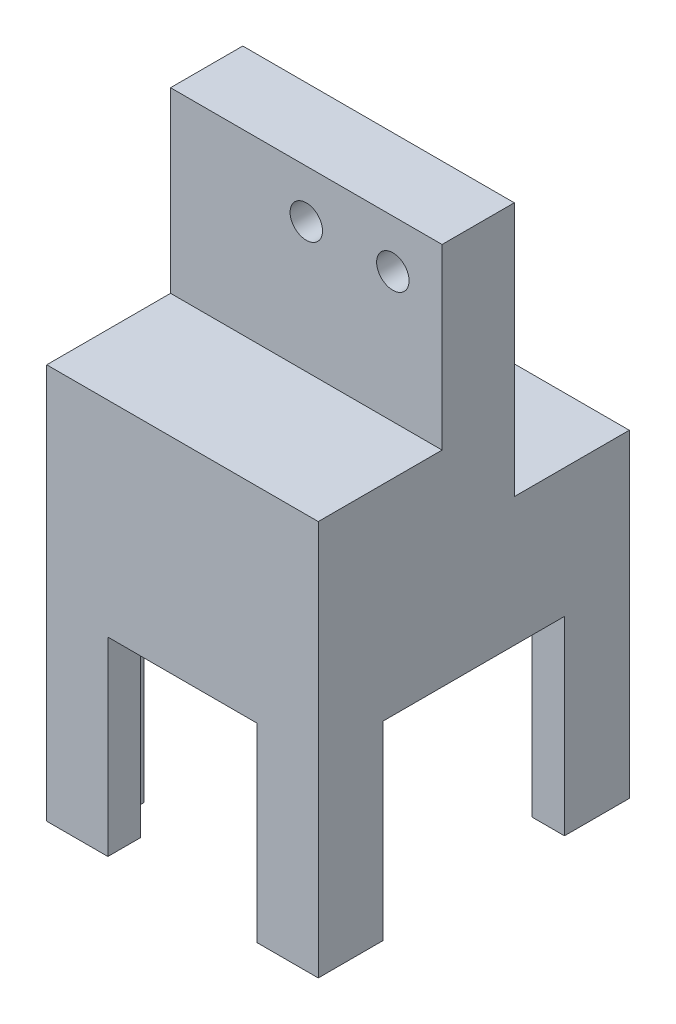
SolidWorks part; units mm, degrees
ref_plane "Front Plane" through (0, 0, 0) normal (0, 0, 1) x (1, 0, 0)
ref_plane "Top Plane" through (0, 0, 0) normal (0, 1, 0) x (1, 0, 0)
ref_plane "Right Plane" through (0, 0, 0) normal (1, 0, 0) x (0, 0, -1)
sketch "Sketch4" plane through (0, 0, 0) normal (0, 1, 0) x (1, 0, 0)
  line L1 (-12.55, 14.375) -> (12.55, 14.375)
  line L2 (-12.55, 14.375) -> (-12.55, -14.375)
  line L3 (-12.55, -14.375) -> (12.55, -14.375)
  line L4 (12.55, 14.375) -> (12.55, -14.375)
  line L5 (-12.55, 14.375) -> (12.55, -14.375) construction
  line L6 (-12.55, -14.375) -> (12.55, 14.375) construction
  point P0 (0, 0)
  dimension "D1" = 28.75
  dimension "D2" = 25.1
extrude "Boss-Extrude2" add sketch "Sketch4" along normal blind 53
sketch "Sketch5" plane through (0, 0, 0) normal (0, -1, 0) x (-1, 0, 0)
  line L0 (-12.55, -14.375) -> (-12.55, 14.375) construction
  line L1 (9.55, -11.375) -> (-9.55, -11.375)
  line L2 (9.55, -11.375) -> (9.55, 11.375)
  line L3 (9.55, 11.375) -> (-9.55, 11.375)
  line L4 (-9.55, -11.375) -> (-9.55, 11.375)
  line L5 (9.55, -11.375) -> (-9.55, 11.375) construction
  line L6 (9.55, 11.375) -> (-9.55, -11.375) construction
  line L7 (-12.55, 14.375) -> (12.55, 14.375) construction
  point P0 (0, 0)
  dimension "D1" = 22.75
  dimension "D2" = 19.1
  dimension "D3" = 3
  dimension "D4" = 3
extrude "Cut-Extrude1" cut sketch "Sketch5" against normal blind 21.67
fillet "Fillet1" radius 4.1 2 edges at (0, 21.67, -11.375) (0, 21.67, 11.375)
sketch "Sketch6" plane through (0, 21.67, 0) normal (0, -1, 0) x (-1, 0, 0)
  line L1 (1.44, 2.55) -> (-1.44, 2.55)
  line L2 (1.44, 2.55) -> (1.44, -2.55)
  line L3 (1.44, -2.55) -> (-1.44, -2.55)
  line L4 (-1.44, 2.55) -> (-1.44, -2.55)
  line L5 (1.44, 2.55) -> (-1.44, -2.55) construction
  line L6 (1.44, -2.55) -> (-1.44, 2.55) construction
  point P0 (0, 0)
  dimension "D1" = 2.88
  dimension "D2" = 5.1
extrude "Cut-Extrude2" cut sketch "Sketch6" against normal blind 4.67
sketch "Sketch7" plane through (12.55, 0, 0) normal (1, 0, 0) x (0, 0, -1)
  line L0 (-14.375, 53) -> (-14.375, 0) construction
  line L1 (-8.3848, -17.57) -> (8.3848, -17.57)
  line L2 (-8.3848, -17.57) -> (-8.3848, 17.57)
  line L3 (-8.3848, 17.57) -> (8.3848, 17.57)
  line L4 (8.3848, -17.57) -> (8.3848, 17.57)
  line L5 (-8.3848, -17.57) -> (8.3848, 17.57) construction
  line L6 (-8.3848, 17.57) -> (8.3848, -17.57) construction
  point P0 (0, 0)
  dimension "D1" = 35.14
  dimension "D2" = 5.9902
extrude "Cut-Extrude3" cut sketch "Sketch7" against normal blind 40
sketch "Sketch8" plane through (0, 0, -14.375) normal (0, 0, -1) x (-1, 0, 0)
  line L0 (12.55, 53) -> (12.55, 0) construction
  line L1 (-6.8992, -17.57) -> (6.8992, -17.57)
  line L2 (-6.8992, -17.57) -> (-6.8992, 17.57)
  line L3 (-6.8992, 17.57) -> (6.8992, 17.57)
  line L4 (6.8992, -17.57) -> (6.8992, 17.57)
  line L5 (-6.8992, -17.57) -> (6.8992, 17.57) construction
  line L6 (-6.8992, 17.57) -> (6.8992, -17.57) construction
  line L7 (-12.55, 53) -> (-12.55, 0) construction
  point P0 (0, 0)
  dimension "D1" = 35.14
  dimension "D2" = 5.6508
  dimension "D3" = 5.6508
extrude "Cut-Extrude4" cut sketch "Sketch8" against normal blind 40
sketch "Sketch9" plane through (-12.55, 0, 0) normal (-1, 0, 0) x (0, 0, 1)
  line L0 (-14.375, 53) -> (14.375, 53) construction
  line L1 (5.875, 53) -> (14.375, 53)
  line L2 (5.875, 53) -> (5.875, 36.54)
  line L3 (5.875, 36.54) -> (14.375, 36.54)
  line L4 (14.375, 53) -> (14.375, 36.54)
  line L5 (14.375, 53) -> (14.375, 0) construction
  dimension "D1" = 16.46
  dimension "D2" = 8.5
extrude "Cut-Extrude5" cut sketch "Sketch9" against normal blind 40
sketch "Sketch10" plane through (-12.55, 0, 0) normal (-1, 0, 0) x (0, 0, 1)
  line L1 (-14.375, 53) -> (-3.7457, 53)
  line L2 (-14.375, 53) -> (-14.375, 29.4765)
  line L3 (-14.375, 29.4765) -> (-3.7457, 29.4765)
  line L4 (-3.7457, 53) -> (-3.7457, 29.4765)
extrude "Cut-Extrude6" cut sketch "Sketch10" against normal blind 40
sketch "Sketch11" plane through (0, 53, 0) normal (0, 1, 0) x (1, 0, 0)
  line L0 (12.55, -5.875) -> (12.55, 3.7457) construction
  line L1 (-12.55, -5.875) -> (12.55, -5.875)
  line L2 (-12.55, -5.875) -> (-12.55, -2.9302)
  line L3 (-12.55, -2.9302) -> (12.55, -2.9302)
  line L4 (12.55, -5.875) -> (12.55, -2.9302)
  dimension "D1" = 2.9448
extrude "Cut-Extrude7" cut sketch "Sketch11" against normal blind 16.46
sketch "Sketch16" plane through (0, 0, 2.9302) normal (0, 0, 1) x (1, 0, 0)
  circle A0 centre (0, 48.5601) radius 1.5
  circle A1 centre (8, 48.5601) radius 1.5
  dimension "D1" = 3
  dimension "D2" = 3
  dimension "D3" = 8
extrude "Cut-Extrude8" cut sketch "Sketch16" against normal blind 10
